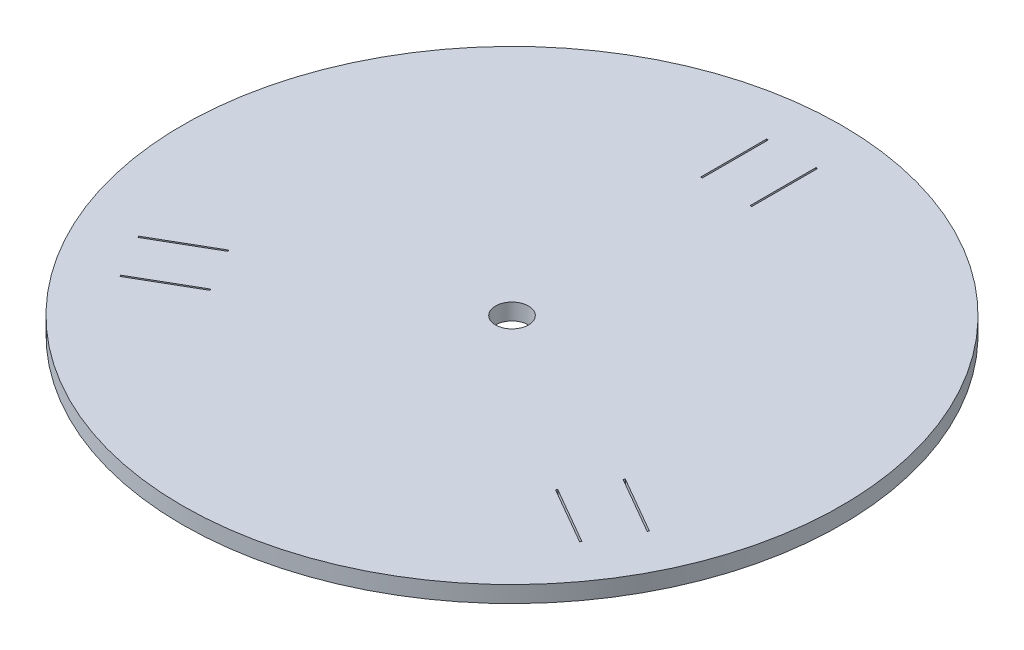
SolidWorks part; units mm, degrees
ref_plane "Front Plane" through (0, 0, 0) normal (0, 0, 1) x (1, 0, 0)
ref_plane "Top Plane" through (0, 0, 0) normal (0, 1, 0) x (1, 0, 0)
ref_plane "Right Plane" through (0, 0, 0) normal (1, 0, 0) x (0, 0, -1)
sketch "Sketch2" plane through (0, 0, 0) normal (0, 1, 0) x (1, 0, 0)
  circle A0 centre (0, 0) radius 100
  dimension "D1" = 200
extrude "Boss-Extrude1" add sketch "Sketch2" along normal blind 5
sketch "Sketch3" plane through (0, 5, 0) normal (0, 1, 0) x (1, 0, 0)
  line L0 (0, 0) -> (0, 100) construction
  line L1 (-7.5, 75) -> (7.5, 75) construction
  line L3 (-7.75, 65) -> (-7.25, 65)
  line L4 (-7.75, 65) -> (-7.75, 85)
  line L5 (-7.75, 85) -> (-7.25, 85)
  line L6 (-7.25, 65) -> (-7.25, 85)
  line L7 (-7.75, 65) -> (-7.25, 85) construction
  line L8 (-7.75, 85) -> (-7.25, 65) construction
  line L9 (7.25, 65) -> (7.75, 65)
  line L10 (7.25, 65) -> (7.25, 85)
  line L11 (7.25, 85) -> (7.75, 85)
  line L12 (7.75, 65) -> (7.75, 85)
  line L13 (7.25, 65) -> (7.75, 85) construction
  line L14 (7.25, 85) -> (7.75, 65) construction
  line L30 (60.1667, -25.7883) -> (77.4872, -35.7883)
  line L31 (60.1667, -25.7883) -> (59.9167, -26.2213)
  line L32 (59.9167, -26.2213) -> (77.2372, -36.2213)
  line L33 (77.4872, -35.7883) -> (77.2372, -36.2213)
  line L34 (52.6667, -38.7787) -> (69.9872, -48.7787)
  line L35 (52.6667, -38.7787) -> (52.4167, -39.2117)
  line L36 (52.4167, -39.2117) -> (69.7372, -49.2117)
  line L37 (69.9872, -48.7787) -> (69.7372, -49.2117)
  line L38 (-52.4167, -39.2117) -> (-69.7372, -49.2117)
  line L39 (-52.4167, -39.2117) -> (-52.6667, -38.7787)
  line L40 (-52.6667, -38.7787) -> (-69.9872, -48.7787)
  line L41 (-69.7372, -49.2117) -> (-69.9872, -48.7787)
  line L42 (-59.9167, -26.2213) -> (-77.2372, -36.2213)
  line L43 (-59.9167, -26.2213) -> (-60.1667, -25.7883)
  line L44 (-60.1667, -25.7883) -> (-77.4872, -35.7883)
  line L45 (-77.2372, -36.2213) -> (-77.4872, -35.7883)
  circle A0 centre (0, 0) radius 100 construction
  point P8 (0, 75)
  point P17 (0, 0)
  point P34 (0, 0)
  point P36 (0, 0)
  dimension "D1" = 15
  dimension "D2" = 20
  dimension "D3" = 0.5
  dimension "D4" = 75
  dimension "D5" = 3
extrude "Cut-Extrude1" cut sketch "Sketch3" against normal through all
sketch "Sketch4" plane through (0, 0, 0) normal (0, 0, 1) x (1, 0, 0)
  line L0 (-100, 0) -> (0, 0)
  line L1 (0, 0) -> (0, -31.5299)
  line L2 (0, -31.5299) -> (26.4846, -31.5299) construction
  line L3 (-100, 0) -> (-128.8281, 20.1856) construction
  arc A0 (0, -31.5299) -> (-100, 0) centre (0, 142.8148) cw
  dimension "D1" = 35
revolve "Revolve1" [suppressed] add sketch "Sketch4" angle 360 about L1
sketch "Sketch8" plane through (0, 0, 0) normal (0, -1, 0) x (-1, 0, 0)
  point P0 (0, 0)
hole_wizard "Ø10.0mm Dowel Hole1" positions "Sketch8" profile "Sketch7" hole size "Ø10.0" standard "ANSI Metric" end condition through all
sketch "Sketch7" plane through (0, 0, 0) normal (1, 0, 0) x (0, 0, -1)
  line L0 (0, 0) -> (0, 5)
  line L1 (0, 5) -> (5, 5)
  line L2 (5, 5) -> (5, 0.025)
  line L3 (5, 0.025) -> (5.025, 0)
  line L5 (5.025, 0) -> (0, 0)
  line L6 (-5, 0.025) -> (-5.025, 0) construction
  line L11 (0, -6.35) -> (0, 107.95) construction
  dimension "Thru Hole Dia." = 10
  dimension "Thru Hole Depth" = 5
  dimension "Near C'Sink Dia." = 10.05
  dimension "Near C'Sink Angle" = 90
equation "\"Leg_Spacing\"=40"
equation "\"Leaf_Spring_Slot_Width\"=5"
equation "\"Leaf_Spring_Thickness\"=0.2"
equation "\"Inner_Radius\"=75"
equation "\"Camera\"=120"
